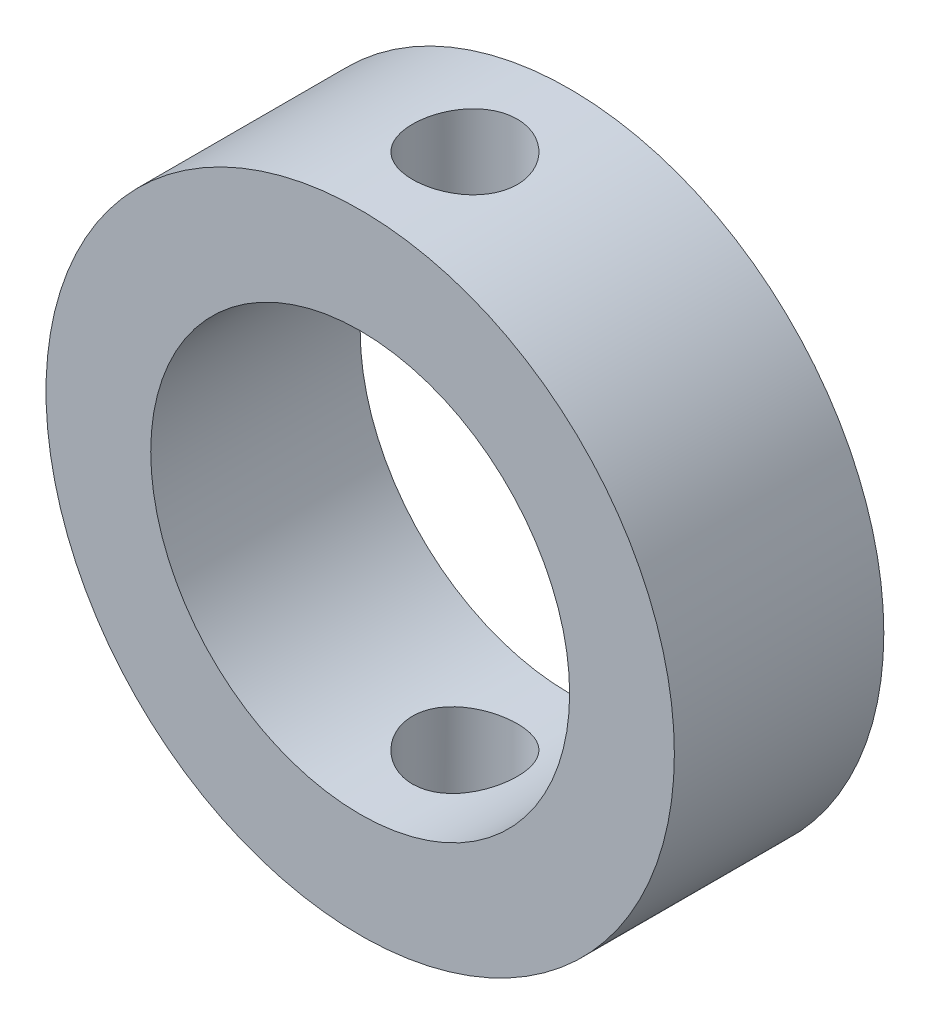
SolidWorks part; units mm, degrees
ref_plane "Front Plane" through (0, 0, 0) normal (0, 0, 1) x (1, 0, 0)
ref_plane "Top Plane" through (0, 0, 0) normal (0, 1, 0) x (1, 0, 0)
ref_plane "Right Plane" through (0, 0, 0) normal (1, 0, 0) x (0, 0, -1)
sketch "Sketch1" plane through (0, 0, 0) normal (0, 0, 1) x (1, 0, 0)
  circle A0 centre (0, 0) radius 15
  circle A1 centre (0, 0) radius 10
  dimension "D1" = 30
  dimension "D2" = 20
extrude "Boss-Extrude2" add sketch "Sketch1" along normal blind 10
sketch "Sketch3" plane through (0, 0, 0) normal (0, 1, 0) x (1, 0, 0)
  circle A0 centre (0, -5) radius 2.5
  dimension "D1" = 5
  dimension "D2" = 5
extrude "Cut-Extrude1" cut sketch "Sketch3" against normal through all both and the other way through all
